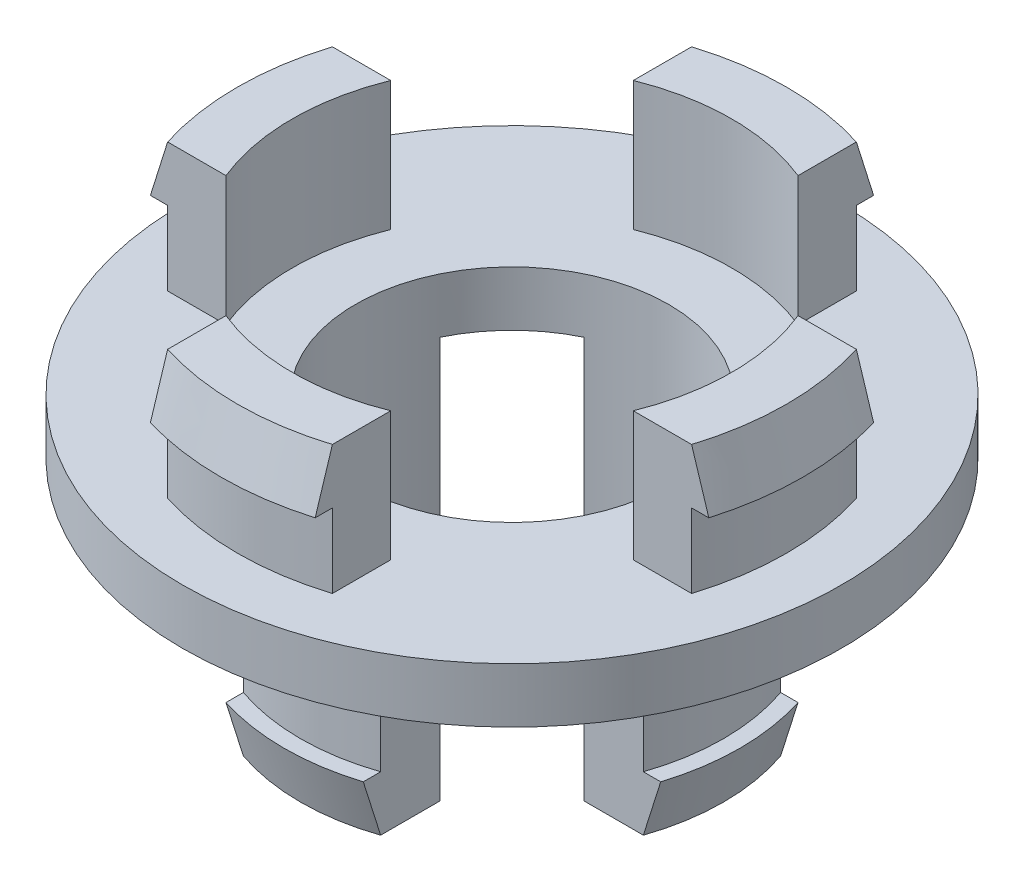
SolidWorks part; units mm, degrees
ref_plane "Front Plane" through (0, 0, 0) normal (0, 0, 1) x (1, 0, 0)
ref_plane "Top Plane" through (0, 0, 0) normal (0, 1, 0) x (1, 0, 0)
ref_plane "Right Plane" through (0, 0, 0) normal (1, 0, 0) x (0, 0, -1)
sketch "Sketch1" plane through (0, 0, 0) normal (0, 0, 1) x (1, 0, 0)
  line L0 (0, 0) -> (0, 8.42) construction
  line L1 (12.7, 17.399) -> (13.462, 14.859)
  line L2 (13.462, 14.859) -> (12.7, 14.859)
  line L3 (12.7, 14.859) -> (12.7, 11.43)
  line L4 (12.7, 11.43) -> (15.24, 11.43)
  line L5 (15.24, 11.43) -> (15.24, 8.89)
  line L6 (15.24, 8.89) -> (9.779, 8.89)
  line L7 (9.779, 8.89) -> (9.779, 2.54)
  line L8 (9.779, 2.54) -> (10.541, 2.54)
  line L9 (10.541, 2.54) -> (9.779, 0)
  line L10 (9.779, 0) -> (7.239, 0)
  line L11 (7.239, 0) -> (7.239, 11.43)
  line L12 (7.239, 11.43) -> (10.16, 11.43)
  line L13 (10.16, 11.43) -> (10.16, 17.399)
  line L14 (10.16, 17.399) -> (12.7, 17.399)
  point P2 (0, 0)
  point P18 (12.7, 13.1445)
  dimension "D1" = 2.54
  dimension "D2" = 2.54
  dimension "D3" = 9.779
  dimension "D4" = 12.7
  dimension "D5" = 2.54
  dimension "D6" = 2.54
  dimension "D7" = 0.762
  dimension "D8" = 2.54
  dimension "D9" = 3.429
  dimension "D10" = 6.35
  dimension "D11" = 2.54
  dimension "D12" = 2.54
revolve "Revolve1" add sketch "Sketch1" angle 360 about L0
sketch "Sketch2" plane through (0, 17.399, 0) normal (0, 1, 0) x (1, 0, 0)
  line L0 (0, 0) -> (-4.7109, 0) construction
  line L1 (-9.4186, 3.81) -> (-12.9116, 3.81)
  line L2 (-12.9116, -3.81) -> (-9.4186, -3.81)
  line L3 (3.81, 9.4186) -> (3.81, 12.9116)
  line L4 (-3.81, 12.9116) -> (-3.81, 9.4186)
  line L5 (9.4186, -3.81) -> (12.9116, -3.81)
  line L6 (12.9116, 3.81) -> (9.4186, 3.81)
  line L7 (-3.81, -9.4186) -> (-3.81, -12.9116)
  line L8 (3.81, -12.9116) -> (3.81, -9.4186)
  circle A0 centre (0, 0) radius 10.16 construction
  circle A1 centre (0, 0) radius 13.462 construction
  circle A2 centre (0, 0) radius 10.16 construction
  arc A3 (-12.9116, -3.81) -> (-3.81, -12.9116) centre (0, 0) ccw
  arc A4 (-9.4186, -3.81) -> (-3.81, -9.4186) centre (0, 0) ccw
  arc A5 (3.81, -9.4186) -> (9.4186, -3.81) centre (0, 0) ccw
  arc A6 (3.81, -12.9116) -> (12.9116, -3.81) centre (0, 0) ccw
  arc A7 (9.4186, 3.81) -> (3.81, 9.4186) centre (0, 0) ccw
  arc A8 (12.9116, 3.81) -> (3.81, 12.9116) centre (0, 0) ccw
  arc A9 (-3.81, 9.4186) -> (-9.4186, 3.81) centre (0, 0) ccw
  arc A10 (-3.81, 12.9116) -> (-12.9116, 3.81) centre (0, 0) ccw
  point P29 (0, 0)
  dimension "D1" = 7.62
  dimension "D2" = 4
extrude "Cut-Extrude1" cut sketch "Sketch2" against normal up to surface (5.969 mm away) up to face at (0, 11.43, -12.7)
sketch "Sketch3" plane through (0, 0, 0) normal (0, -1, 0) x (1, 0, 0)
  line L0 (0, 0) -> (-4.9755, 0) construction
  line L1 (-6.5056, 3.175) -> (-10.0515, 3.175)
  line L2 (-6.5056, -3.175) -> (-10.0515, -3.175)
  line L3 (3.175, 6.5056) -> (3.175, 10.0515)
  line L4 (-3.175, 6.5056) -> (-3.175, 10.0515)
  line L5 (6.5056, -3.175) -> (10.0515, -3.175)
  line L6 (6.5056, 3.175) -> (10.0515, 3.175)
  line L7 (-3.175, -6.5056) -> (-3.175, -10.0515)
  line L8 (3.175, -6.5056) -> (3.175, -10.0515)
  circle A0 centre (0, 0) radius 7.239 construction
  circle A1 centre (0, 0) radius 10.541 construction
  arc A2 (-6.5056, -3.175) -> (-3.175, -6.5056) centre (0, 0) ccw
  arc A3 (-10.0515, -3.175) -> (-3.175, -10.0515) centre (0, 0) ccw
  arc A4 (3.175, -6.5056) -> (6.5056, -3.175) centre (0, 0) ccw
  arc A5 (3.175, -10.0515) -> (10.0515, -3.175) centre (0, 0) ccw
  arc A6 (6.5056, 3.175) -> (3.175, 6.5056) centre (0, 0) ccw
  arc A7 (10.0515, 3.175) -> (3.175, 10.0515) centre (0, 0) ccw
  arc A8 (-3.175, 6.5056) -> (-6.5056, 3.175) centre (0, 0) ccw
  arc A9 (-3.175, 10.0515) -> (-10.0515, 3.175) centre (0, 0) ccw
  point P27 (0, 0)
  dimension "D1" = 6.35
  dimension "D2" = 4
extrude "Cut-Extrude2" cut sketch "Sketch3" against normal up to surface (8.89 mm away) up to face at (0, 8.89, -15.24)
